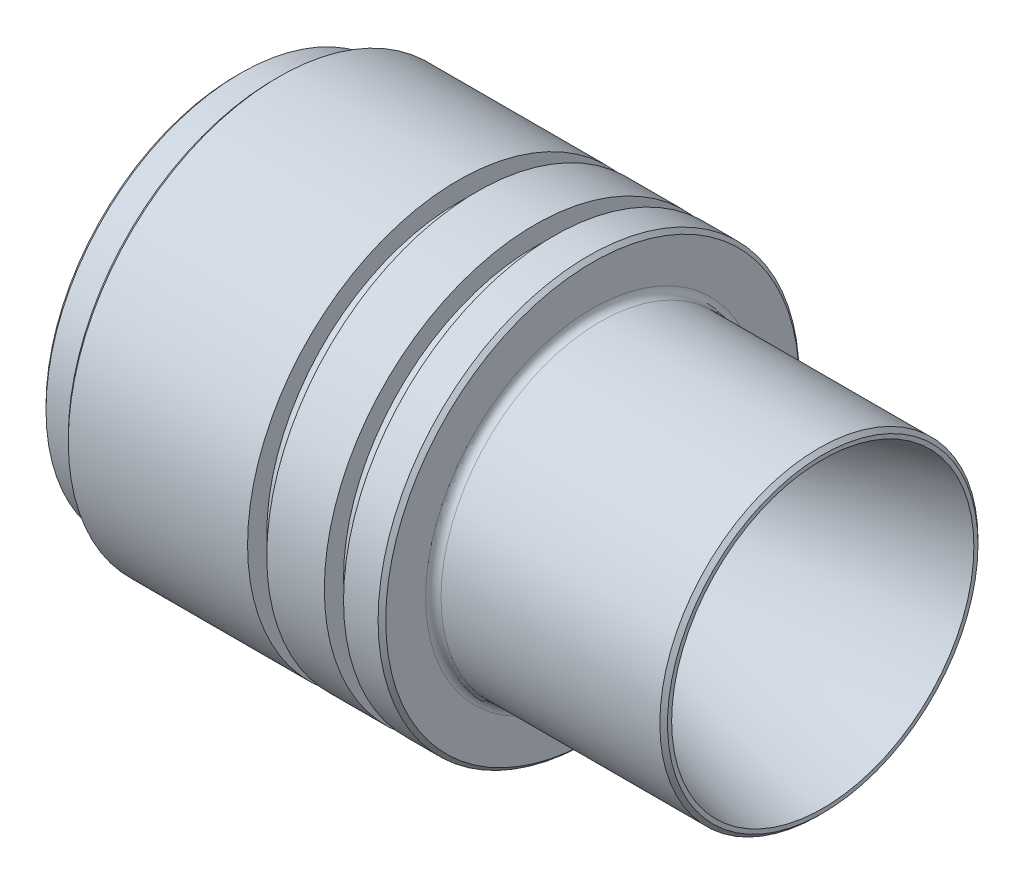
SolidWorks part; units mm, degrees
material "C (Graphite)"
ref_plane "Front Plane" through (0, 0, 0) normal (0, 0, 1) x (1, 0, 0)
ref_plane "Top Plane" through (0, 0, 0) normal (0, 1, 0) x (1, 0, 0)
ref_plane "Right Plane" through (0, 0, 0) normal (1, 0, 0) x (0, 0, -1)
ref_axis "Axis1" through (-88.99, 0, 0) along (1, 0, 0)
sketch "Sketch1" plane through (0, 0, 0) normal (0, 0, 1) x (1, 0, 0)
  line L0 (0, 0) -> (58.8686, 0) construction
  line L1 (-88.99, 0) -> (96.1394, 0) construction
  line L2 (0, -34.8234) -> (0, 34.8234) construction
  line L3 (-31.75, 32.1564) -> (-38.1, 32.1564)
  line L4 (58.8686, 25) -> (83.019, 29.6944) construction
  line L5 (-31.75, 32.1564) -> (-31.75, 34.8234)
  line L6 (-31.75, 34.8234) -> (-1.4564, 34.8234)
  line L7 (-1.4564, 34.8234) -> (-1.4564, 31.6484)
  line L8 (-1.4564, 31.6484) -> (1.7186, 31.6484)
  line L9 (1.7186, 31.6484) -> (1.7186, 34.8234)
  line L10 (1.7186, 34.8234) -> (11.2436, 34.8234)
  line L11 (11.2436, 34.8234) -> (11.2436, 31.6484)
  line L12 (11.2436, 31.6484) -> (14.4186, 31.6484)
  line L13 (14.4186, 31.6484) -> (14.4186, 34.8234)
  line L14 (14.4186, 34.8234) -> (20.7686, 34.8234)
  line L15 (20.7686, 34.8234) -> (20.7686, 26.3144)
  line L16 (20.7686, 26.3144) -> (58.8686, 26.3144)
  line L17 (58.8686, 26.3144) -> (58.8686, 25)
  line L18 (58.8686, 25) -> (58.8686, -25) construction
  line L19 (83.019, 29.6944) -> (83.019, 25) construction
  line L20 (8.3825, 8.5) -> (8.3825, 11.802) construction
  line L21 (8.3825, 8.5) -> (8.3825, -8.5) construction
  line L22 (8.3825, 11.802) -> (8.3825, 21.2) construction
  line L23 (9.7779, 8.8094) -> (29.5604, 18.0341) construction
  line L24 (58.8686, -26.3144) -> (58.8686, -25)
  line L25 (20.7686, -26.3144) -> (58.8686, -26.3144)
  line L26 (83.019, 25) -> (58.8686, 25) construction
  line L36 (-38.1, -32.1564) -> (-38.1, -28.4734)
  line L37 (-31.75, -32.1564) -> (-38.1, -32.1564)
  line L38 (-38.1, 32.1564) -> (-38.1, 28.4734)
  line L39 (-38.1, 28.4734) -> (-28.8659, 28.4734)
  line L40 (-31.75, -32.1564) -> (-31.75, -34.8234)
  line L41 (-31.75, -34.8234) -> (-1.4564, -34.8234)
  line L42 (8.3825, 8.5) -> (58.8686, 8.5) construction
  line L43 (29.5604, 18.0341) -> (29.5604, 8.8094) construction
  line L44 (29.5604, 8.8094) -> (9.7779, 8.8094) construction
  arc A0 (8.3825, 8.5) -> (9.7779, 8.8094) centre (8.3825, 11.802) ccw
  arc A1 (8.3825, 8.5) -> (-2.1959, 14.1724) centre (8.3825, 21.2) cw
  arc A2 (-2.1959, 14.1724) -> (-28.8659, 28.4734) centre (-28.8659, -3.5456) ccw
  parabola Q0 (58.8686, 25) -> (9.7779, 8.8094) focus (91.9746, -64.3417) apex (89.2749, 28.3918)
  point P25 (8.3825, 0)
  dimension "D16" = 12.7
  dimension "D17" = 3.302
  dimension "D1" = 8.5
  dimension "D2" = 6.35
  dimension "D3" = 3.175
  dimension "D4" = 3.175
  dimension "D5" = 9.525
  dimension "D6" = 38.1
  dimension "D7" = 6.35
  dimension "D8" = 69.6468
  dimension "D9" = 8.509
  dimension "D10" = 64.3128
  dimension "D11" = 26.67
  dimension "D12" = 25
  dimension "D13" = 6.35
  dimension "D14" = 8.3825
  dimension "D15" = 38.1
  dimension "D18" = 11
  dimension "D19" = 25
revolve "Revolve1" add sketch "Sketch1" angle 360 about axis through (-88.99, 0, 0) along (1, 0, 0)
chamfer "Chamfer1" distance 0.635 angle 45 4 edges at (58.8686, 0, 26.3144) (20.7686, 0, 34.8234) (-31.75, 0, 34.8234) (-38.1, 0, 32.1564)
fillet "Fillet1" radius 1.27 1 edges at (20.7686, 0, 26.3144)
equation "\"throat_radius\"= 8.5mm"
equation "\"diverg_circle_rad\"= 0.382 * \"throat_radius\""
equation "\"converg_circle_rad\"= 1.5 * \"throat_radius\""
